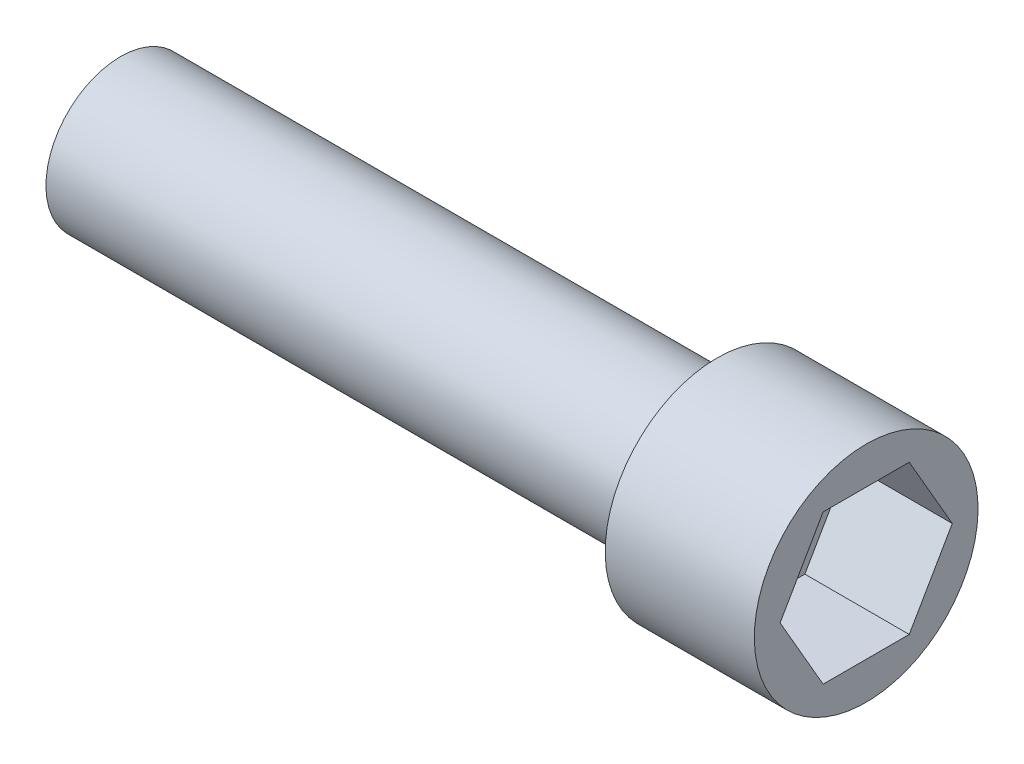
SolidWorks part; units mm, degrees
material "AISI 1010 Steel, hot rolled bar"
ref_plane "Front Plane" through (0, 0, 0) normal (0, 0, 1) x (1, 0, 0)
ref_plane "Top Plane" through (0, 0, 0) normal (0, 1, 0) x (1, 0, 0)
ref_plane "Right Plane" through (0, 0, 0) normal (1, 0, 0) x (0, 0, -1)
sketch "Sketch1" plane through (0, 0, 0) normal (0, 0, 1) x (1, 0, 0)
  line L0 (0, 0) -> (0, 5)
  line L1 (0, 5) -> (40, 5)
  line L2 (40, 5) -> (40, 7.5)
  line L3 (40, 7.5) -> (50, 7.5)
  line L4 (50, 7.5) -> (50, 0)
  line L5 (50, 0) -> (0, 0)
  dimension "D1" = 5
  dimension "D2" = 10
  dimension "D3" = 7.5
  dimension "D4" = 40
revolve "Revolve1" add sketch "Sketch1" angle 360 about L5
sketch "Sketch5" plane through (50, 0, 0) normal (1, 0, 0) x (0, 0, -1)
  line L1 (5.7735, 0) -> (2.8868, 5)
  line L2 (2.8868, 5) -> (-2.8868, 5)
  line L3 (-2.8868, 5) -> (-5.7735, 0)
  line L4 (-5.7735, 0) -> (-2.8868, -5)
  line L5 (-2.8868, -5) -> (2.8868, -5)
  line L6 (2.8868, -5) -> (5.7735, 0)
  circle A0 centre (0, 0) radius 5 construction
  dimension "D1" = 10
extrude "Cut-Extrude2" cut sketch "Sketch5" against normal blind 7 contours L1 L2 L3 L4 L5 L6
